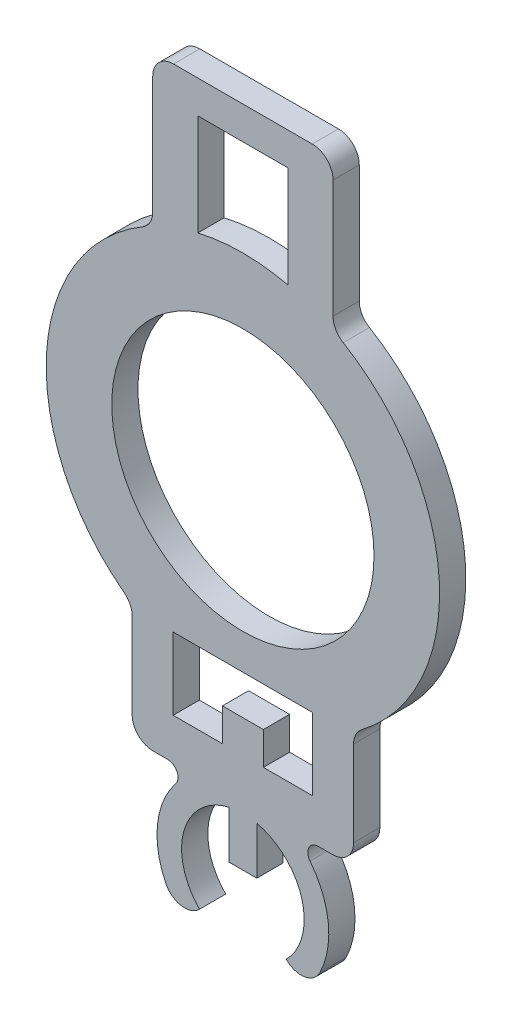
SolidWorks part; units mm, degrees
material "Delrin 2700 NC010, Low Viscosity Acetal Copolymer (SS)"
ref_plane "Front Plane" through (0, 0, 0) normal (0, 0, 1) x (1, 0, 0)
ref_plane "Top Plane" through (0, 0, 0) normal (0, 1, 0) x (1, 0, 0)
ref_plane "Right Plane" through (0, 0, 0) normal (1, 0, 0) x (0, 0, -1)
sketch "Sketch1" plane through (0, 0, 0) normal (0, 0, 1) x (1, 0, 0)
  line L0 (-2.6446, -2.6446) -> (2.6446, -2.6446) construction
  line L1 (-2.6446, -2.6446) -> (-3.7052, -3.7052)
  line L2 (3.7052, -3.7052) -> (2.6446, -2.6446)
  line L4 (-1.5, 12.7962) -> (-1.5, 5.7962)
  line L5 (-3, 14.2962) -> (3, 14.2962)
  line L6 (-3, 14.2962) -> (-3, 4.2962)
  line L7 (-3, 4.2962) -> (3, 4.2962)
  line L8 (3, 14.2962) -> (3, 4.2962)
  line L9 (-3, 14.2962) -> (3, 4.2962) construction
  line L10 (-3, 4.2962) -> (3, 14.2962) construction
  line L11 (-1.5, 5.7962) -> (1.5, 5.7962)
  line L12 (1.5, 12.7962) -> (1.5, 5.7962)
  line L13 (-1.5, 12.7962) -> (1.5, 12.7962)
  line L15 (0.85, 3.74) -> (-0.85, 3.74)
  line L16 (0.85, 3.74) -> (0.85, 0.74)
  line L17 (0.85, 0.74) -> (-0.85, 0.74)
  line L18 (-0.85, 3.74) -> (-0.85, 0.74)
  line L19 (0.85, 3.74) -> (-0.85, 0.74) construction
  line L20 (0.85, 0.74) -> (-0.85, 3.74) construction
  arc A0 (-2.6446, -2.6446) -> (2.6446, -2.6446) centre (0, 0) cw
  arc A1 (-3.7052, -3.7052) -> (0, 5.24) centre (0, 0) cw
  arc A2 (0, 5.24) -> (3.7052, -3.7052) centre (0, 0) cw
  arc A3 (-3.7052, -3.7052) -> (3.7052, -3.7052) centre (0, 0) cw construction
  point P8 (0, 9.2962)
  point P12 (0, 3.74)
  point P20 (0, 2.24)
  dimension "D1" = 3.74
  dimension "D3" = 1.5
  dimension "D6" = 1.5
  dimension "D8" = 3
  dimension "D2" = 90
  dimension "D4" = 10
  dimension "D5" = 6
  dimension "D7" = 1.7
sketch "Sketch2" plane through (0, 0, 0) normal (0, 0, 1) x (1, 0, 0)
  line L0 (-5.5, 37.5336) -> (-2.75, 37.5336) construction
  line L1 (2.75, 37.5336) -> (5.5, 37.5336) construction
  line L2 (-4.2545, 8.0596) -> (-1.25, 8.0596) construction
  line L3 (-5.5, 32.0165) -> (-5.5, 41.2211)
  line L4 (-5.5, 41.2211) -> (5.5, 41.2211)
  line L5 (5.5, 41.2211) -> (5.5, 32.0165)
  line L6 (-2.75, 39.2211) -> (2.75, 39.2211)
  line L7 (1.25, 8.0596) -> (4.2545, 8.0596) construction
  line L8 (-0.85, 2.9853) -> (-6.7545, 2.9853) construction
  line L9 (0.85, 2.9853) -> (6.7545, 2.9853) construction
  line L10 (2.75, 39.2211) -> (2.75, 33.0318)
  line L11 (8, 12.4068) -> (8, 30.2954) construction
  line L12 (-2.75, 39.2211) -> (-2.75, 33.0318)
  line L13 (-3, 4.2962) -> (-6.7545, 4.2962)
  line L14 (5, 15.1061) -> (5, 27.5961) construction
  line L15 (-1.25, 6.7962) -> (-1.25, 8.7962)
  line L16 (-4.2545, 6.7962) -> (-4.2545, 11.1962)
  line L17 (4.2545, 11.1962) -> (-4.2545, 11.1962)
  line L18 (4.2545, 6.7962) -> (4.2545, 11.1962)
  line L19 (4.2545, 6.7962) -> (1.25, 6.7962)
  line L20 (6.7545, 4.2962) -> (6.7545, 11.4326)
  line L21 (6.7545, 4.2962) -> (3, 4.2962)
  line L22 (-6.7545, 4.2962) -> (-6.7545, 11.4326)
  line L23 (-6.7545, 4.2962) -> (-6.7545, 11.1962) construction
  line L24 (6.7545, 4.2962) -> (6.7545, 11.1962) construction
  line L25 (-1.25, 8.7962) -> (1.25, 8.7962)
  line L26 (-1.25, 6.7962) -> (-4.2545, 6.7962)
  line L27 (0, 31.6088) -> (0, -38.2577) construction
  line L28 (4.2545, 6.7962) -> (-4.2545, 6.7962) construction
  line L29 (6.7545, 4.2962) -> (-6.7545, 4.2962) construction
  line L32 (1.25, 6.7962) -> (1.25, 8.7962)
  line L34 (5, 12.4068) -> (5, 30.2954) construction
  line L35 (-3.7052, -3.7052) -> (-2.6446, -2.6446)
  line L36 (2.6446, -2.6446) -> (3.7052, -3.7052)
  line L45 (-3.7052, -3.7052) -> (-2.6446, -2.6446)
  line L46 (2.6446, -2.6446) -> (3.7052, -3.7052)
  line L49 (0.85, 3.74) -> (-0.85, 3.74)
  line L50 (-0.85, 3.74) -> (-0.85, 0.74)
  line L51 (-0.85, 0.74) -> (0.85, 0.74)
  line L52 (0.85, 0.74) -> (0.85, 3.74)
  line L54 (-0.85, 3.6421) -> (-0.85, 0.74)
  line L55 (-0.85, 0.74) -> (0.85, 0.74)
  line L56 (0.85, 0.74) -> (0.85, 3.6421)
  circle A0 centre (0, 21.3511) radius 8
  arc A1 (6.7545, 11.4326) -> (5.5, 32.0165) centre (0, 21.3511) ccw
  arc A2 (-0.85, 3.6421) -> (-2.6446, -2.6446) centre (0, 0) ccw
  arc A3 (2.75, 33.0318) -> (-2.75, 33.0318) centre (0, 21.3511) ccw
  arc A4 (-5.5, 32.0165) -> (-6.7545, 11.4326) centre (0, 21.3511) ccw
  arc A7 (0, 5.24) -> (-3.7052, -3.7052) centre (0, 0) ccw
  arc A8 (3.7052, -3.7052) -> (0, 5.24) centre (0, 0) ccw
  arc A9 (2.6446, -2.6446) -> (-2.6446, -2.6446) centre (0, 0) ccw
  arc A10 (-3, 4.2962) -> (-3.7052, -3.7052) centre (0, 0) ccw
  arc A11 (3.7052, -3.7052) -> (3, 4.2962) centre (0, 0) ccw
  arc A12 (2.6446, -2.6446) -> (0.85, 3.6421) centre (0, 0) ccw
  point P31 (0, 31.6088)
  dimension "D1" = 16
  dimension "D2" = 24
  dimension "D3" = 11
  dimension "D4" = 19.87
  dimension "D5" = 2
  dimension "D6" = 2.5
  dimension "D11" = 8.509
  dimension "D12" = 4.4
  dimension "D13" = 10.1549
  dimension "D14" = 2.5
  dimension "D15" = 2
  dimension "D16" = 0
  dimension "D17" = 3
  dimension "D18" = 0
extrude "Boss-Extrude1" add sketch "Sketch2" along normal blind 1.6
fillet "Fillet1" radius 0.635 2 edges at (3, 4.2962, 0.8) (-3, 4.2962, 0.8)
fillet "Fillet2" radius 1.27 10 edges at (-5.5, 32.0165, 0.8) (5.5, 32.0165, 0.8) (-3.7052, -3.7052, 0.8) (3.7052, -3.7052, 0.8) (6.7545, 4.2962, 0.8) (-6.7545, 4.2962, 0.8) (-6.7545, 11.4326, 0.8) (6.7545, 11.4326, 0.8) (-5.5, 41.2211, 0.8) (5.5, 41.2211, 0.8)
